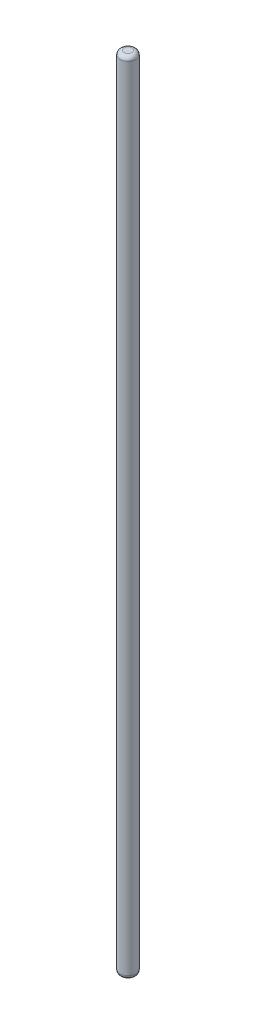
SolidWorks part; units mm, degrees
ref_plane "Front Plane" through (0, 0, 0) normal (0, 0, 1) x (1, 0, 0)
ref_plane "Top Plane" through (0, 0, 0) normal (0, 1, 0) x (1, 0, 0)
ref_plane "Right Plane" through (0, 0, 0) normal (1, 0, 0) x (0, 0, -1)
sketch "Sketch1" plane through (0, 0, 0) normal (0, 1, 0) x (1, 0, 0)
  circle A0 centre (0, 0) radius 3
  dimension "D1" = 6
extrude "Boss-Extrude1" add sketch "Sketch1" along normal blind 300
fillet "Fillet1" radius 1.5 2 edges at (0, 300, 3) (0, 0, 3)
